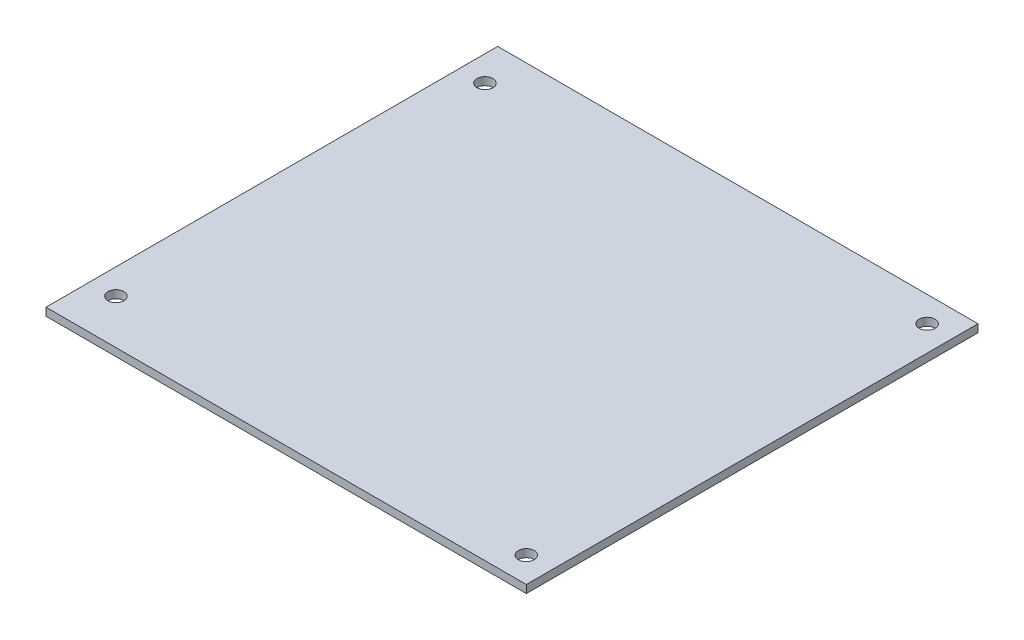
SolidWorks part; units mm, degrees
material "E-Glass Fiber"
ref_plane "Front Plane" through (0, 0, 0) normal (0, 0, 1) x (1, 0, 0)
ref_plane "Top Plane" through (0, 0, 0) normal (0, 1, 0) x (1, 0, 0)
ref_plane "Right Plane" through (0, 0, 0) normal (1, 0, 0) x (0, 0, -1)
sketch "Sketch1" plane through (0, 0, 0) normal (0, 1, 0) x (1, 0, 0)
  line L1 (47.945, -45.085) -> (-47.945, -45.085)
  line L2 (47.945, -45.085) -> (47.945, 45.085)
  line L3 (47.945, 45.085) -> (-47.945, 45.085)
  line L4 (-47.945, -45.085) -> (-47.945, 45.085)
  line L5 (47.945, -45.085) -> (-47.945, 45.085) construction
  line L6 (47.945, 45.085) -> (-47.945, -45.085) construction
  point P0 (0, 0)
  dimension "D1" = 90.17
  dimension "D2" = 95.89
extrude "Boss-Extrude1" add sketch "Sketch1" along normal blind 1.57
sketch "Sketch2" plane through (0, 1.57, 0) normal (0, 1, 0) x (1, 0, 0)
  line L0 (-47.945, -45.085) -> (47.945, -45.085) construction
  line L1 (47.945, -45.085) -> (47.945, 45.085) construction
  circle A0 centre (42.865, -40.005) radius 1.59
  circle A1 centre (-42.865, -36.195) radius 1.59
  circle A2 centre (-42.865, 37.465) radius 1.59
  circle A3 centre (42.865, 40.005) radius 1.59
  dimension "D3" = 3.18
  dimension "D6" = 3.18
  dimension "D9" = 3.18
  dimension "D12" = 3.18
  dimension "D1" = 5.08
  dimension "D2" = 5.08
  dimension "D4" = 8.89
  dimension "D5" = 90.81
  dimension "D7" = 5.08
  dimension "D8" = 85.09
  dimension "D10" = 90.81
  dimension "D11" = 82.55
extrude "Cut-Extrude1" cut sketch "Sketch2" against normal through all
